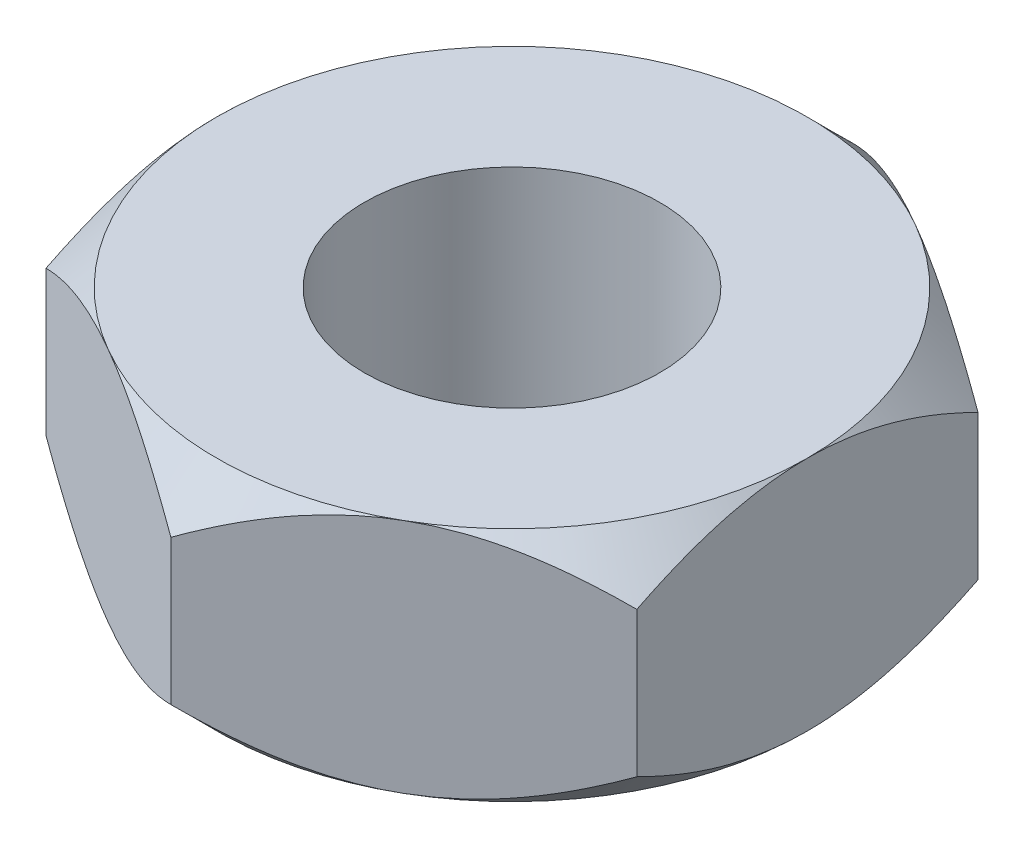
SolidWorks part; units mm, degrees
material "Stainless Steel (ferritic)"
ref_plane "Front Plane" through (0, 0, 0) normal (0, 0, 1) x (1, 0, 0)
ref_plane "Top Plane" through (0, 0, 0) normal (0, 1, 0) x (1, 0, 0)
ref_plane "Right Plane" through (0, 0, 0) normal (1, 0, 0) x (0, 0, -1)
sketch "Sketch1" plane through (0, 0, 0) normal (0, 1, 0) x (1, 0, 0)
  line L1 (0, -2.3094) -> (2, -1.1547)
  line L2 (2, -1.1547) -> (2, 1.1547)
  line L3 (2, 1.1547) -> (0, 2.3094)
  line L4 (0, 2.3094) -> (-2, 1.1547)
  line L5 (-2, 1.1547) -> (-2, -1.1547)
  line L6 (-2, -1.1547) -> (0, -2.3094)
  circle A0 centre (0, 0) radius 2 construction
  circle A1 centre (0, 0) radius 1
  dimension "D1" = 4
extrude "Boss-Extrude1" add sketch "Sketch1" along normal mid plane 1.6
cosmetic thread "Cosmetic Thread3" parameters "D2"=2.5
sketch "Sketch4" plane through (0, 0.8, 0) normal (0, 1, 0) x (1, 0, 0)
  line L0 (-2, 1.1547) -> (-2, -1.1547) construction
  circle A0 centre (0, 0) radius 2
extrude "Cut-Extrude1" cut sketch "Sketch4" against normal blind 1.6 draft 45 flip side to cut
mirror "Mirror1" about plane through (0, 0, 0) normal (0, 1, 0) of "Cut-Extrude1"
